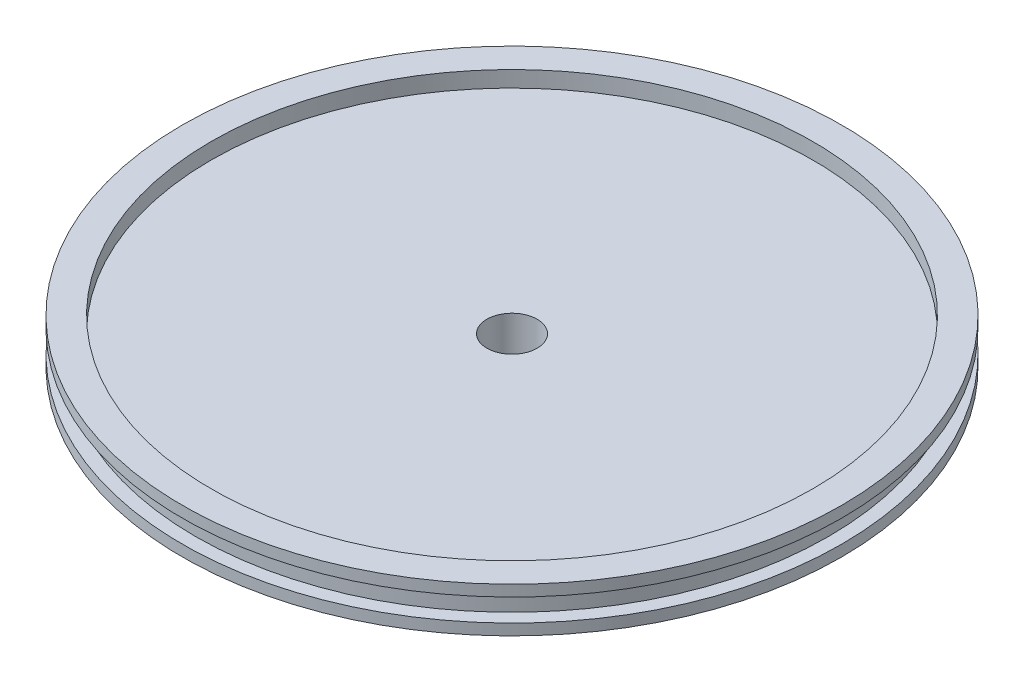
SolidWorks part; units mm, degrees
material "6061-T6 (SS)"
ref_plane "Front Plane" through (0, 0, 0) normal (0, 0, 1) x (1, 0, 0)
ref_plane "Top Plane" through (0, 0, 0) normal (0, 1, 0) x (1, 0, 0)
ref_plane "Right Plane" through (0, 0, 0) normal (1, 0, 0) x (0, 0, -1)
sketch "Sketch1" plane through (0, 0, 0) normal (0, 0, 1) x (1, 0, 0)
  line L0 (0, 48.1922) -> (0, -25.6743) construction
  line L1 (0, 0) -> (72.898, 0)
  line L2 (72.898, 0) -> (72.898, 2.4638)
  line L3 (72.898, 2.4638) -> (69.977, 2.4638)
  line L4 (69.977, 2.4638) -> (69.977, 7.4422)
  line L5 (69.977, 7.4422) -> (72.898, 7.4422)
  line L6 (72.898, 7.4422) -> (72.898, 9.906)
  line L7 (72.898, 9.906) -> (66.548, 9.906)
  line L8 (66.548, 9.906) -> (66.548, 6.35)
  line L9 (66.548, 6.35) -> (0, 6.35)
  line L10 (0, 6.35) -> (0, 0)
  point P11 (66.548, 9.906)
  point P14 (66.548, 9.6855)
  dimension "D1" = 145.796
  dimension "D2" = 4.9784
  dimension "D3" = 2.921
  dimension "D4" = 9.906
  dimension "D5" = 6.35
  dimension "D6" = 6.35
revolve "Revolve1" add sketch "Sketch1" angle 360 about L0
sketch "Sketch6" plane through (0, 0, 0) normal (0, -1, 0) x (1, 0, 0)
  circle A0 centre (0, 0) radius 66.04
  dimension "D1" = 132.08
extrude "Boss-Extrude1" add sketch "Sketch6" along normal blind 2.54
hole_wizard "Pipe Tap Drill for 1/4 Tap - GN2" positions "Sketch2" profile "Sketch3" hole size "1/4" standard "ANSI Inch" end condition through all
sketch "Sketch2" plane through (0, 6.35, 0) normal (0, 1, 0) x (1, 0, 0)
  point P4 (0, 0)
  dimension "D1" = 0
sketch "Sketch3" plane through (0, 6.35, 0) normal (1, 0, 0) x (0, 0, 1)
  line L0 (0, 0) -> (0, 8.89)
  line L1 (0, 8.89) -> (5.5626, 8.89)
  line L2 (5.5626, 8.89) -> (5.5626, 0)
  line L5 (5.5626, 0) -> (0, 0)
  line L11 (0, -6.35) -> (0, 107.95) construction
  dimension "Thru Hole Dia." = 11.1252
  dimension "Thru Hole Depth" = 8.89
fillet "CNC ID Fillet" [suppressed] radius 0.1778
fillet "CNC OD Fillet" [suppressed] radius 0.127
chamfer "CNC Chamfers" [suppressed] distance 0.254 angle 45
fillet "CNC Bore Fillet" [suppressed] radius 0.254
